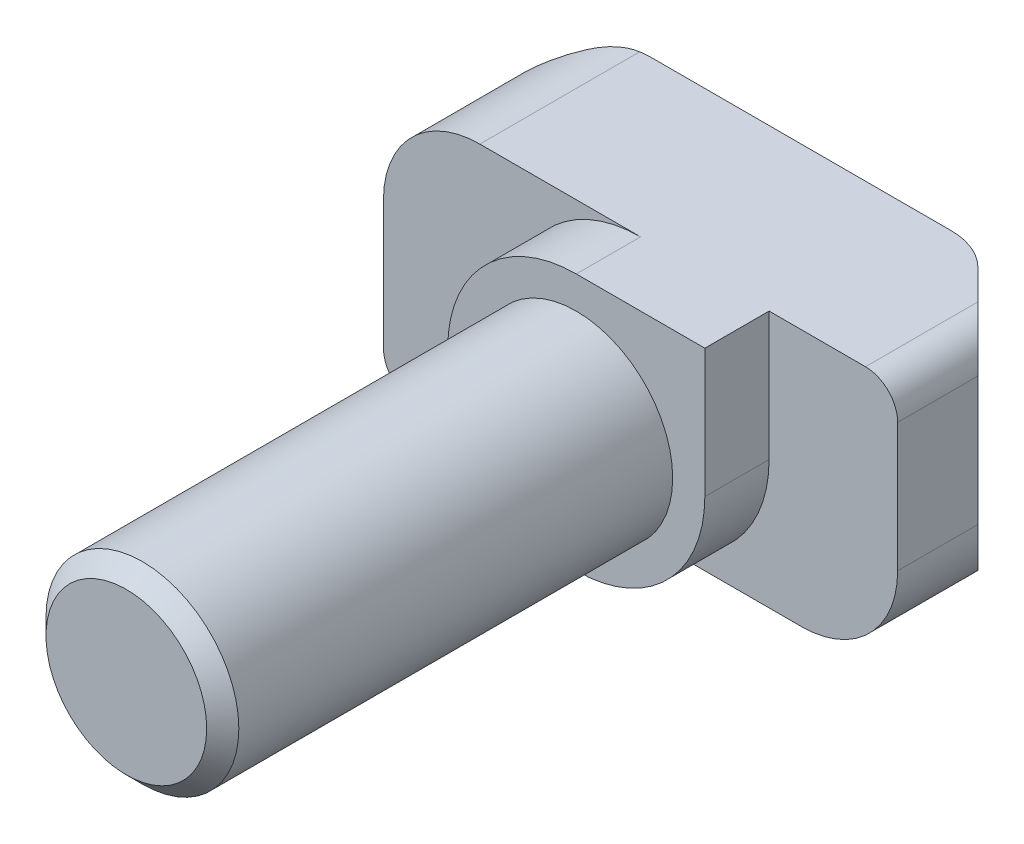
SolidWorks part; units mm, degrees
ref_plane "前视基准面" through (0, 0, 0) normal (0, 0, 1) x (1, 0, 0)
ref_plane "上视基准面" through (0, 0, 0) normal (0, 1, 0) x (1, 0, 0)
ref_plane "右视基准面" through (0, 0, 0) normal (1, 0, 0) x (0, 0, -1)
other "Configuration Table"
ref_plane "基准面1" through (0, 4, 0) normal (0, 1, 0) x (1, 0, 0)
sketch "草图1" plane through (0, 4, 0) normal (0, 1, 0) x (1, 0, 0)
  line L0 (-8, -7) -> (8, -7)
  line L1 (8, -7) -> (8, -2.5)
  line L2 (8, -2.5) -> (5.5, 0)
  line L3 (5.5, 0) -> (-5.5, 0)
  line L4 (-5.5, 0) -> (-8, -2.5)
  line L5 (-8, -2.5) -> (-8, -7)
extrude "凸台-拉伸1" add sketch "草图1" against normal blind 8
sketch "草图2" plane through (0, -4, 0) normal (0, -1, 0) x (1, 0, 0)
  line L0 (-8, 5) -> (-4, 5)
  line L1 (-4, 5) -> (-4, 7)
  line L2 (-4, 7) -> (-8, 7)
  line L3 (-8, 7) -> (-8, 5)
extrude "切除-拉伸1" cut sketch "草图2" against normal through all
sketch "草图3" plane through (0, -4, 0) normal (0, -1, 0) x (1, 0, 0)
  line L0 (4, 5) -> (8, 5)
  line L1 (8, 5) -> (8, 7)
  line L2 (8, 7) -> (4, 7)
  line L3 (4, 7) -> (4, 5)
extrude "切除-拉伸2" cut sketch "草图3" against normal through all
sketch "草图4" plane through (0, 0, 0) normal (0, 1, 0) x (1, 0, 0)
  line L0 (3, -7) -> (0, -7)
  line L1 (0, -7) -> (0, -21)
  line L2 (0, -21) -> (3, -21)
  line L3 (3, -21) -> (3, -7)
  line L4 (0, -7) -> (0, -21) construction
revolve "旋转1" add sketch "草图4" angle 360 about L4
chamfer "倒角1" distance 0.5 angle 45 1 edges at (3, 0, 21)
fillet "圆角1" radius 1 2 edges at (8, 4, 3.75) (-8, -4, 3.75)
fillet "圆角2" radius 2 2 edges at (5.5, 0, 0) (-5.5, 0, 0)
fillet "圆角3" radius 3 2 edges at (8, -4, 3.75) (-8, 4, 3.75)
fillet "圆角4" radius 4 2 edges at (4, -4, 6) (-4, 4, 6)
